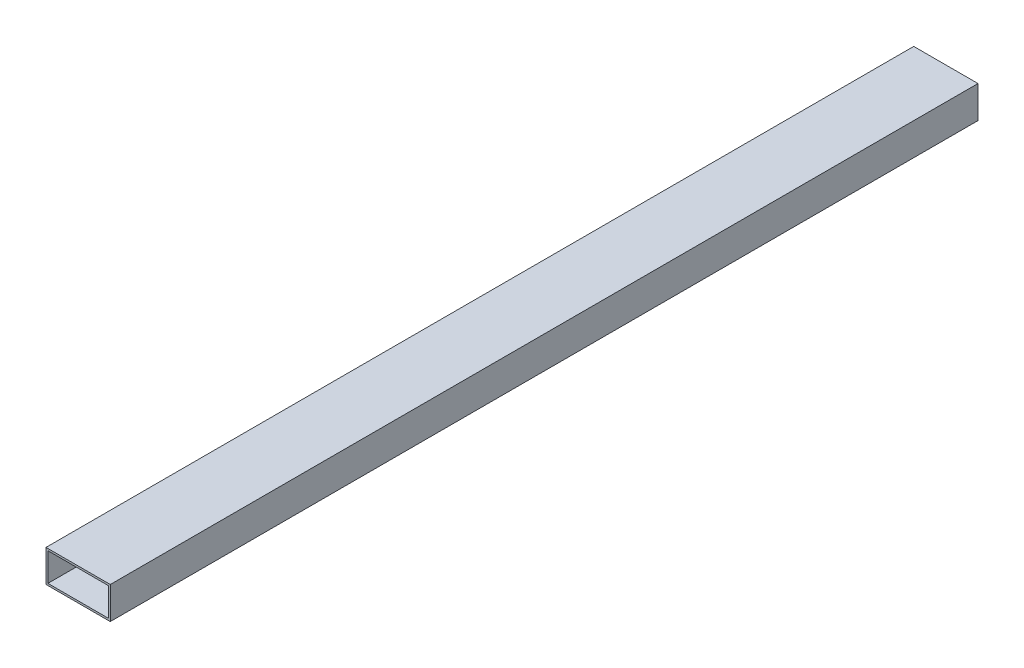
SolidWorks part; units mm, degrees
ref_plane "Front Plane" through (0, 0, 0) normal (0, 0, 1) x (1, 0, 0)
ref_plane "Top Plane" through (0, 0, 0) normal (0, 1, 0) x (1, 0, 0)
ref_plane "Right Plane" through (0, 0, 0) normal (1, 0, 0) x (0, 0, -1)
sketch "Sketch2" plane through (0, 0, 0) normal (0, 0, 1) x (1, 0, 0)
  line L1 (0, 0) -> (-50.8, 0)
  line L2 (0, 0) -> (0, 25.4)
  line L3 (0, 25.4) -> (-50.8, 25.4)
  line L4 (-50.8, 0) -> (-50.8, 25.4)
  dimension "D1" = 50.8
  dimension "D2" = 25.4
extrude "Extrude-Thin1" add sketch "Sketch2" along normal blind 685.8 thin
